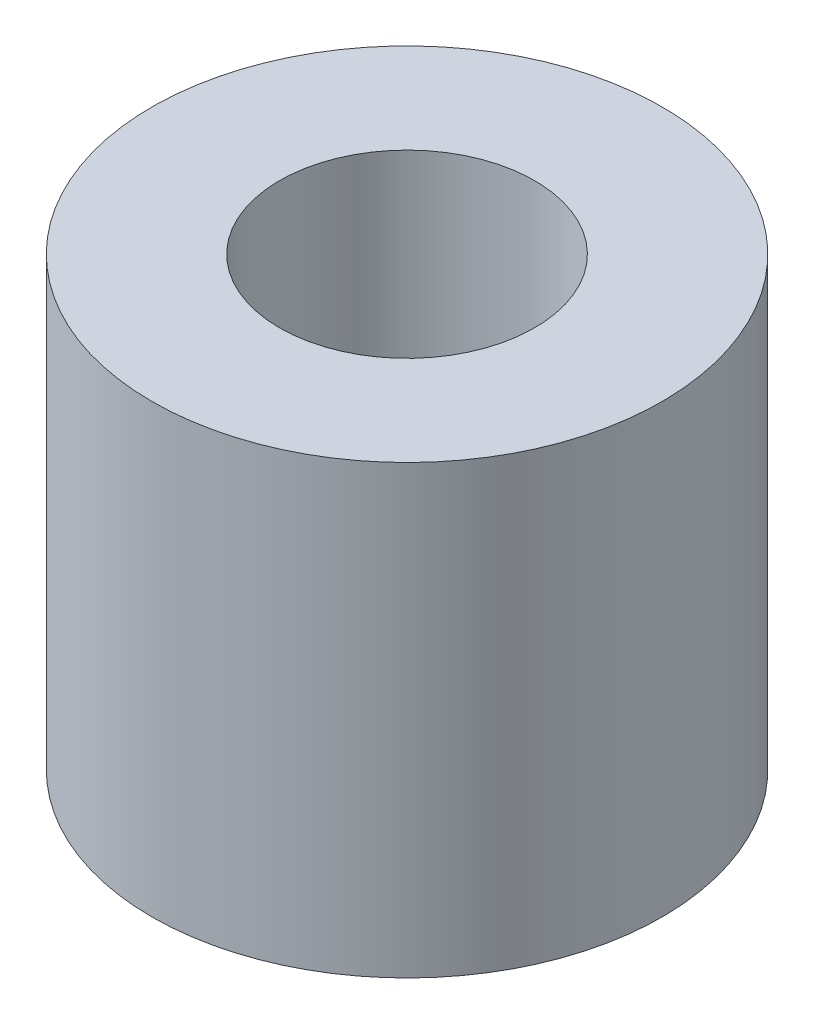
SolidWorks part; units mm, degrees
ref_plane "Front Plane" through (0, 0, 0) normal (0, 0, 1) x (1, 0, 0)
ref_plane "Top Plane" through (0, 0, 0) normal (0, 1, 0) x (1, 0, 0)
ref_plane "Right Plane" through (0, 0, 0) normal (1, 0, 0) x (0, 0, -1)
sketch "Sketch1" plane through (0, 0, 0) normal (0, 1, 0) x (1, 0, 0)
  circle A0 centre (0, 0) radius 2
  circle A1 centre (0, 0) radius 4
  dimension "D1" = 8
  dimension "D2" = 4
extrude "Boss-Extrude1" add sketch "Sketch1" along normal blind 7
